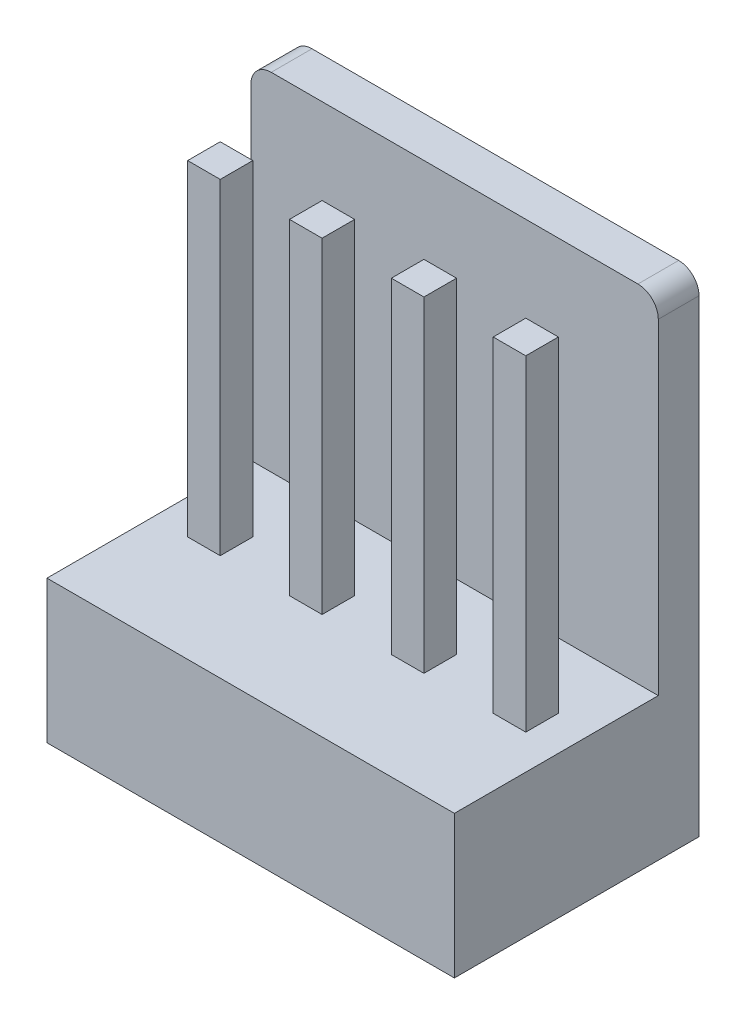
SolidWorks part; units mm, degrees
material "ABS"
ref_plane "Front" through (0, 0, 0) normal (0, 0, 1) x (1, 0, 0)
ref_plane "Top" through (0, 0, 0) normal (0, 1, 0) x (1, 0, 0)
ref_plane "Right" through (0, 0, 0) normal (1, 0, 0) x (0, 0, -1)
sketch "Esboço1" plane through (0, 0, 0) normal (0, 1, 0) x (1, 0, 0)
  line L1 (-5, -3.0025) -> (5, -3.0025)
  line L2 (-5, -3.0025) -> (-5, 3.0025)
  line L3 (-5, 3.0025) -> (5, 3.0025)
  line L4 (5, -3.0025) -> (5, 3.0025)
  line L5 (-5, -3.0025) -> (5, 3.0025) construction
  line L6 (-5, 3.0025) -> (5, -3.0025) construction
  point P0 (0, 0)
  dimension "D1" = 10
  dimension "D2" = 6.0049
extrude "Ressalto-extrusão1" add sketch "Esboço1" along normal blind 3.5
sketch "Esboço2" plane through (0, 3.5, 0) normal (0, 1, 0) x (1, 0, 0)
  line L0 (5, -3.0025) -> (5, 3.0025) construction
  line L1 (-5, 3.0025) -> (5, 3.0025)
  line L2 (-5, 3.0025) -> (-5, 2.0025)
  line L3 (-5, 2.0025) -> (5, 2.0025)
  line L4 (5, 3.0025) -> (5, 2.0025)
  dimension "D1" = 1
extrude "Ressalto-extrusão2" add sketch "Esboço2" along normal blind 8.5
sketch "Esboço3" plane through (0, 3.5, 0) normal (0, 1, 0) x (1, 0, 0)
  line L0 (1.25, 0) -> (3.75, 0) construction
  line L1 (-3.35, 0.4) -> (-4.15, 0.4)
  line L2 (-3.35, 0.4) -> (-3.35, -0.4)
  line L3 (-3.35, -0.4) -> (-4.15, -0.4)
  line L4 (-4.15, 0.4) -> (-4.15, -0.4)
  line L5 (-3.35, 0.4) -> (-4.15, -0.4) construction
  line L6 (-3.35, -0.4) -> (-4.15, 0.4) construction
  line L7 (-0.85, 0.4) -> (-1.65, 0.4)
  line L8 (-0.85, 0.4) -> (-0.85, -0.4)
  line L9 (-0.85, -0.4) -> (-1.65, -0.4)
  line L10 (-1.65, 0.4) -> (-1.65, -0.4)
  line L11 (-0.85, 0.4) -> (-1.65, -0.4) construction
  line L12 (-0.85, -0.4) -> (-1.65, 0.4) construction
  line L13 (1.65, 0.4) -> (0.85, 0.4)
  line L14 (1.65, 0.4) -> (1.65, -0.4)
  line L15 (1.65, -0.4) -> (0.85, -0.4)
  line L16 (0.85, 0.4) -> (0.85, -0.4)
  line L17 (1.65, 0.4) -> (0.85, -0.4) construction
  line L18 (1.65, -0.4) -> (0.85, 0.4) construction
  line L19 (4.15, 0.4) -> (3.35, 0.4)
  line L20 (4.15, 0.4) -> (4.15, -0.4)
  line L21 (4.15, -0.4) -> (3.35, -0.4)
  line L22 (3.35, 0.4) -> (3.35, -0.4)
  line L23 (4.15, 0.4) -> (3.35, -0.4) construction
  line L24 (4.15, -0.4) -> (3.35, 0.4) construction
  line L25 (-3.75, 0) -> (-1.25, 0) construction
  line L26 (0, 1.9191) -> (0, -0.0833) construction
  line L27 (-1.25, 0) -> (1.25, 0) construction
  point P0 (-3.75, 0)
  point P5 (-1.25, 0)
  point P10 (1.25, 0)
  point P15 (3.75, 0)
  point P21 (2.9878, 0)
  point P27 (3.7244, 0)
  dimension "D1" = 0.8
  dimension "D2" = 2.5
extrude "Ressalto-extrusão3" add sketch "Esboço3" along normal blind 8
fillet "Filete1" radius 0.5 2 edges at (-5, 12, -2.5025) (5, 12, -2.5025)
